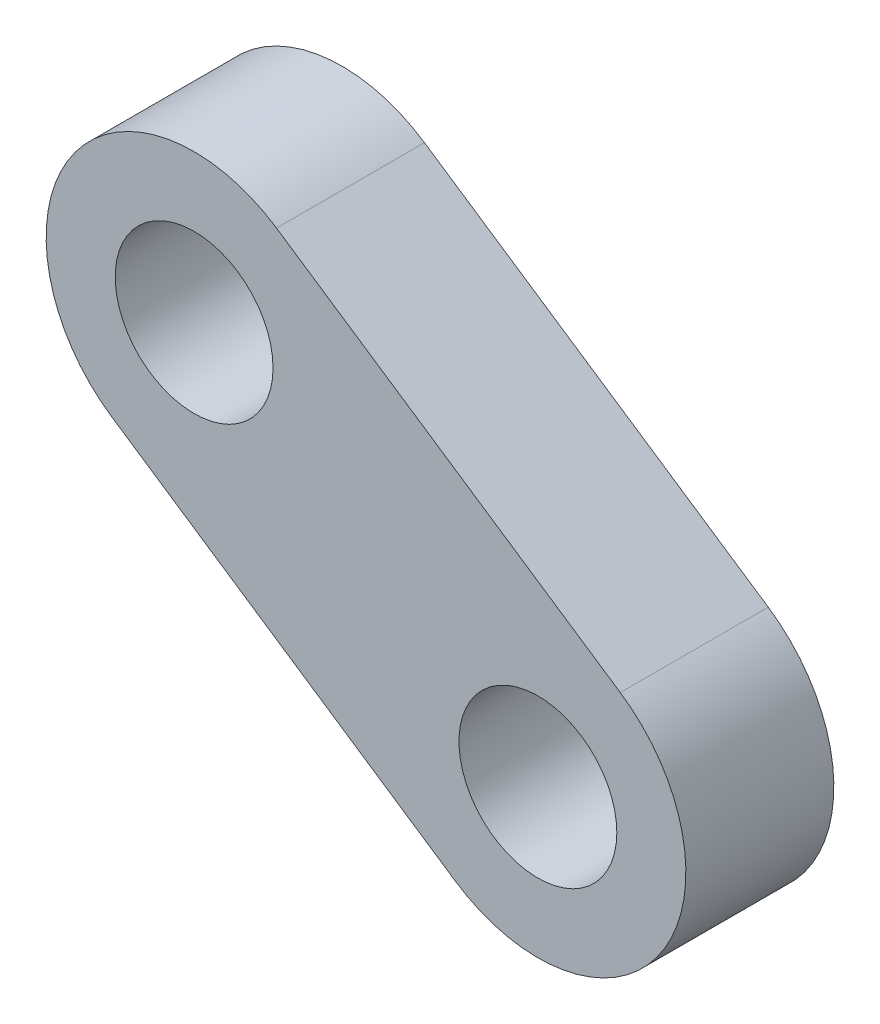
SolidWorks part; units mm, degrees
ref_plane "Front Plane" through (0, 0, 0) normal (0, 0, 1) x (1, 0, 0)
ref_plane "Top Plane" through (0, 0, 0) normal (0, 1, 0) x (1, 0, 0)
ref_plane "Right Plane" through (0, 0, 0) normal (1, 0, 0) x (0, 0, -1)
sketch "Sketch1" plane through (0, 0, 0) normal (0, 0, 1) x (1, 0, 0)
  line L1 (-20.8958, 27.7508) -> (-13.9263, 23.0801)
  line L2 (-17.5556, 32.7351) -> (-10.5861, 28.0644)
  circle A1 centre (-19.2257, 30.243) radius 1.6
  circle A3 centre (-12.2562, 25.5722) radius 1.6
  arc A4 (-17.5556, 32.7351) -> (-20.8958, 27.7508) centre (-19.2257, 30.243) ccw
  arc A5 (-13.9263, 23.0801) -> (-10.5861, 28.0644) centre (-12.2562, 25.5722) ccw
  point P13 (-12.2562, 25.5722)
extrude "Boss-Extrude1" add sketch "Sketch1" along normal blind 3
